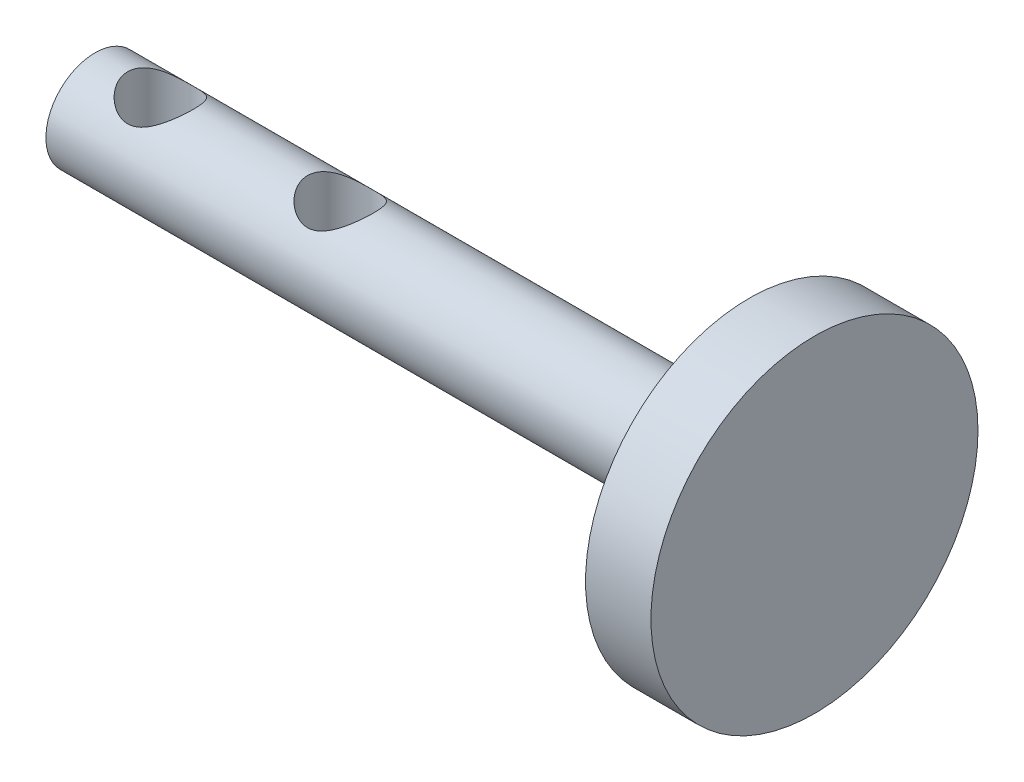
SolidWorks part; units mm, degrees
ref_plane "Front Plane" through (0, 0, 0) normal (0, 0, 1) x (1, 0, 0)
ref_plane "Top Plane" through (0, 0, 0) normal (0, 1, 0) x (1, 0, 0)
ref_plane "Right Plane" through (0, 0, 0) normal (1, 0, 0) x (0, 0, -1)
sketch "Sketch1" plane through (0, 0, 0) normal (1, 0, 0) x (0, 0, -1)
  circle A4 centre (0, 0) radius 1.5
  dimension "D1" = 3
extrude "Boss-Extrude4" add sketch "Sketch1" along normal blind 20
sketch "Sketch5" plane through (20, 0, 0) normal (1, 0, 0) x (0, 0, -1)
  line L0 (0, -1.5) -> (0, -5) construction
  circle A0 centre (0, 0) radius 5
  circle A1 centre (0, 0) radius 1.5 construction
  dimension "D1" = 3.5
extrude "Boss-Extrude5" add sketch "Sketch5" along normal blind 2
sketch "Sketch6" plane through (0, 0, 0) normal (0, 1, 0) x (1, 0, 0)
  line L0 (0, 0) -> (14.1821, 0) construction
  line L1 (0, 1.5) -> (0, -1.5) construction
  line L2 (3, 0) -> (6.5, 0) construction
  circle A0 centre (2, 0) radius 1
  circle A1 centre (7.5, 0) radius 1
  dimension "D3" = 2
  dimension "D4" = 2
  dimension "D1" = 3.5
  dimension "D2" = 2
extrude "Cut-Extrude1" cut sketch "Sketch6" against normal through all both and the other way through all
